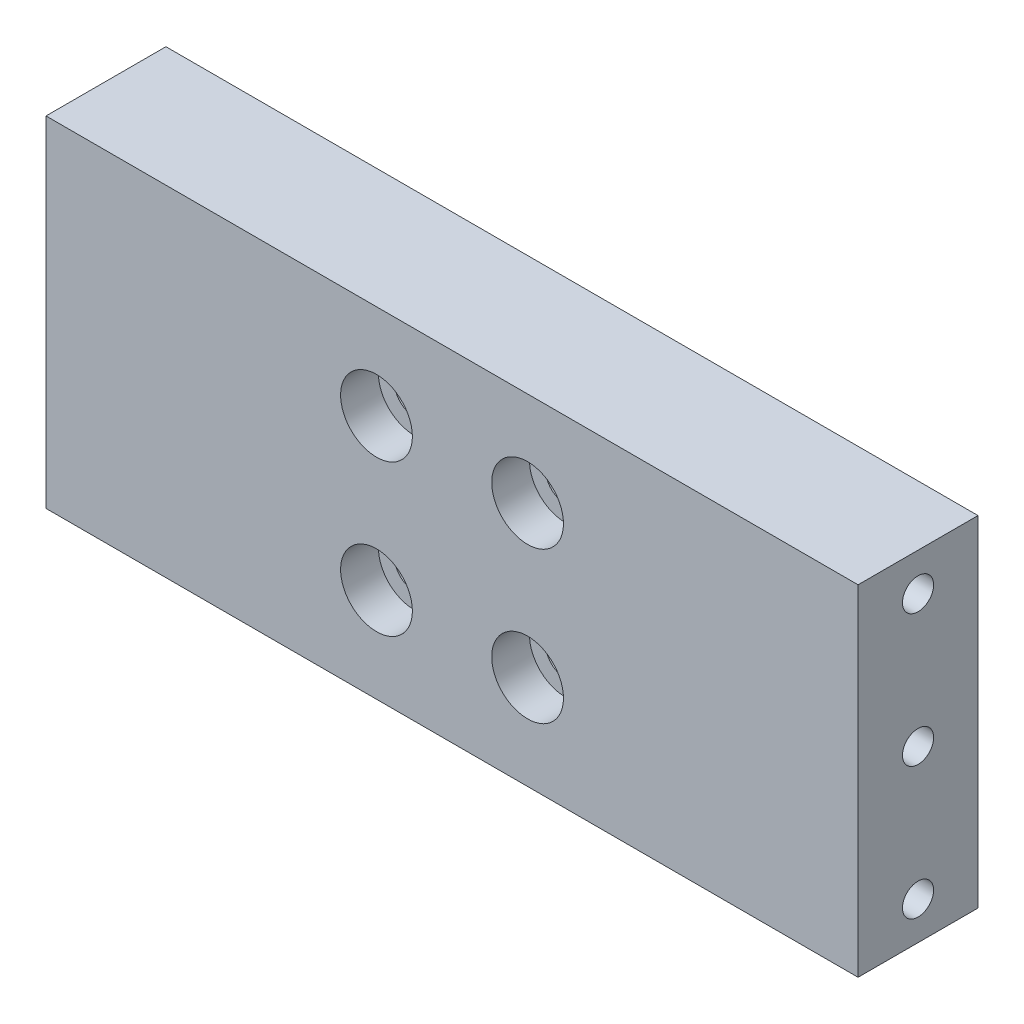
SolidWorks part; units mm, degrees
ref_plane "Front Plane" through (0, 0, 0) normal (0, 0, 1) x (1, 0, 0)
ref_plane "Top Plane" through (0, 0, 0) normal (0, 1, 0) x (1, 0, 0)
ref_plane "Right Plane" through (0, 0, 0) normal (1, 0, 0) x (0, 0, -1)
sketch "Sketch1" plane through (0, 0, 0) normal (0, 0, 1) x (1, 0, 0)
  line L1 (43, -18) -> (-43, -18)
  line L2 (43, -18) -> (43, 18)
  line L3 (43, 18) -> (-43, 18)
  line L4 (-43, -18) -> (-43, 18)
  line L5 (43, -18) -> (-43, 18) construction
  line L6 (43, 18) -> (-43, -18) construction
  point P0 (0, 0)
  dimension "D1" = 36
  dimension "D2" = 86
extrude "Boss-Extrude1" add sketch "Sketch1" along normal mid plane 12.7
sketch "Sketch2" plane through (0, 0, 6.35) normal (0, 0, 1) x (1, 0, 0)
  line L1 (-8, -8) -> (8, -8) construction
  line L2 (-8, -8) -> (-8, 8) construction
  line L3 (-8, 8) -> (8, 8) construction
  line L4 (8, -8) -> (8, 8) construction
  line L5 (-8, -8) -> (8, 8) construction
  line L6 (-8, 8) -> (8, -8) construction
  circle A0 centre (-8, 8) radius 2.1
  circle A1 centre (8, 8) radius 2.1
  circle A2 centre (8, -8) radius 2.1
  circle A3 centre (-8, -8) radius 2.1
  point P0 (0, 0)
  point P6 (0, 0)
  point P16 (0, 0)
  dimension "D2" = 4.2
  dimension "D1" = 16
  dimension "D3" = 4
hole_wizard "CBORE for M4 Hex Head Cap Screw2" positions "3DSketch3" profile "Sketch5" counterbore size "M4" standard "ISO" end condition through all
sketch3d "3DSketch3"
  point P0 (-8, 8, 6.35)
  point P3 (-8, -8, 6.35)
  point P6 (8, -8, 6.35)
  point P9 (8, 8, 6.35)
sketch "Sketch5" plane through (-8, 8, 6.35) normal (1, 0, 0) x (0, -1, 0)
  line L0 (0, 0) -> (0, 12.7)
  line L1 (0, 12.7) -> (2.1, 12.7)
  line L3 (2.1, 12.7) -> (2.1, 4)
  line L4 (2.1, 4) -> (3.8, 4)
  line L5 (3.8, 4) -> (3.8, 0)
  line L7 (3.8, 0) -> (0, 0)
  line L11 (0, -6.35) -> (0, 107.95) construction
  dimension "Thru Hole Dia." = 4.2
  dimension "Thru Hole Depth" = 12.7
  dimension "C'Bore Dia." = 7.6
  dimension "C'Bore Depth" = 4
sketch "Sketch6" plane through (-43, 0, 0) normal (-1, 0, 0) x (0, 0, 1)
  line L0 (0, 14) -> (0, -14) construction
  circle A0 centre (0, 14) radius 1.65
  circle A1 centre (0, -14) radius 1.65
  circle A2 centre (0, 0) radius 1.65
  point P3 (0, 0)
  dimension "D2" = 3.3
  dimension "D3" = 3.3
  dimension "D4" = 3.3
  dimension "D1" = 28
extrude "Cut-Extrude1" cut sketch "Sketch6" against normal blind 10
mirror "Mirror1" about plane through (0, 0, 0) normal (1, 0, 0) of "Cut-Extrude1"
